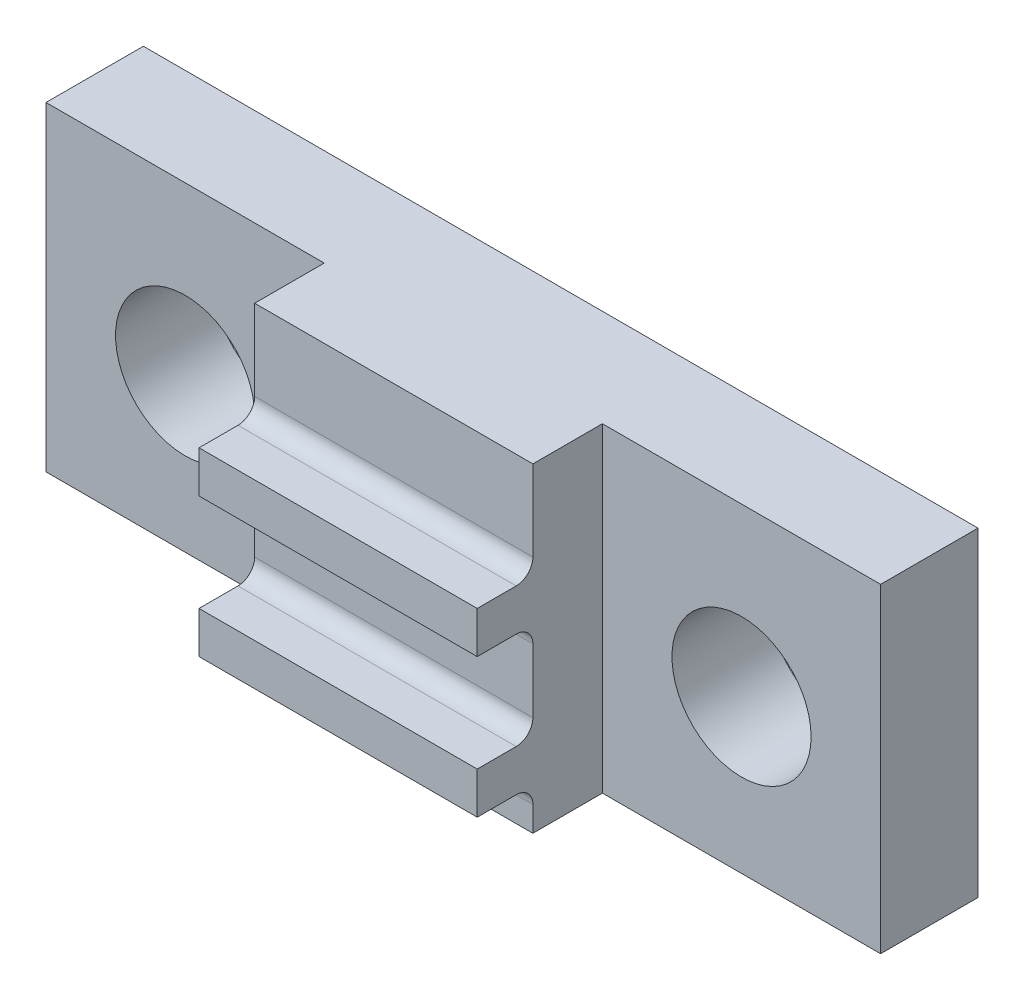
SolidWorks part; units mm, degrees
ref_plane "Front Plane" through (0, 0, 0) normal (0, 0, 1) x (1, 0, 0)
ref_plane "Top Plane" through (0, 0, 0) normal (0, 1, 0) x (1, 0, 0)
ref_plane "Right Plane" through (0, 0, 0) normal (1, 0, 0) x (0, 0, -1)
sketch "Sketch1" plane through (0, 0, 0) normal (0, 0, 1) x (1, 0, 0)
  line L1 (-15, 5.75) -> (15, 5.75)
  line L2 (-15, 5.75) -> (-15, -5.75)
  line L3 (-15, -5.75) -> (15, -5.75)
  line L4 (15, 5.75) -> (15, -5.75)
  line L5 (-15, 5.75) -> (15, -5.75) construction
  line L6 (-15, -5.75) -> (15, 5.75) construction
  circle A0 centre (-10, -0.25) radius 2.5
  circle A1 centre (10, -0.25) radius 2.5
  point P0 (0, 0)
  dimension "D3" = 5
  dimension "D6" = 5
  dimension "D1" = 30
  dimension "D2" = 11.5
  dimension "D4" = 5
  dimension "D5" = 5
extrude "Boss-Extrude1" add sketch "Sketch1" along normal blind 3.5
sketch "Sketch2" plane through (0, 0, 3.5) normal (0, 0, 1) x (1, 0, 0)
  line L1 (-15, -5.75) -> (15, -5.75) construction
  line L2 (-5, 5.75) -> (5, 5.75)
  line L3 (-5, 5.75) -> (-5, -5.75)
  line L4 (-5, -5.75) -> (5, -5.75)
  line L5 (5, 5.75) -> (5, -5.75)
  line L6 (-5, 5.75) -> (5, -5.75) construction
  line L7 (-5, -5.75) -> (5, 5.75) construction
  point P0 (0, 0)
  dimension "D1" = 10
extrude "Boss-Extrude2" add sketch "Sketch2" along normal blind 4.5
sketch "Sketch3" plane through (-5, 0, 0) normal (-1, 0, 0) x (0, 0, 1)
  line L0 (8, 5.75) -> (8, -5.75) construction
  line L1 (6, 5.75) -> (8, 5.75)
  line L2 (6, 5.75) -> (6, 2.25)
  line L3 (6, 2.25) -> (8, 2.25)
  line L4 (8, 5.75) -> (8, 2.25)
  line L5 (6, 5.75) -> (8, 2.25) construction
  line L6 (6, 2.25) -> (8, 5.75) construction
  line L7 (8, 5.75) -> (3.5, 5.75) construction
  point P0 (7, 4)
  dimension "D1" = 3.5
  dimension "D2" = 0
  dimension "D3" = 2
extrude "Cut-Extrude1" cut sketch "Sketch3" against normal through all
sketch "Sketch4" plane through (-5, 0, 0) normal (-1, 0, 0) x (0, 0, 1)
  line L0 (8, 2.25) -> (8, -5.75) construction
  line L1 (6, 0.75) -> (8, 0.75)
  line L2 (6, 0.75) -> (6, -2.75)
  line L3 (6, -2.75) -> (8, -2.75)
  line L4 (8, 0.75) -> (8, -2.75)
  line L5 (6, 0.75) -> (8, -2.75) construction
  line L6 (6, -2.75) -> (8, 0.75) construction
  line L7 (6, 2.25) -> (8, 2.25) construction
  line L8 (6, -4.25) -> (6, -7.75)
  line L9 (6, -4.25) -> (8, -4.25)
  line L10 (8, -4.25) -> (8, -7.75)
  line L11 (6, -7.75) -> (8, -7.75)
  point P0 (7, -1)
  dimension "D1" = 3.5
  dimension "D2" = 2
  dimension "D3" = 1.5
  dimension "D4" = 2
extrude "Cut-Extrude2" cut sketch "Sketch4" against normal up to surface (10 mm away) up to face at (5, -0.2083, 6.4167)
fillet "Fillet2" radius 0.6 4 edges at (0, -4.25, 6) (0, -2.75, 6) (0, 0.75, 6) (0, 2.25, 6)
